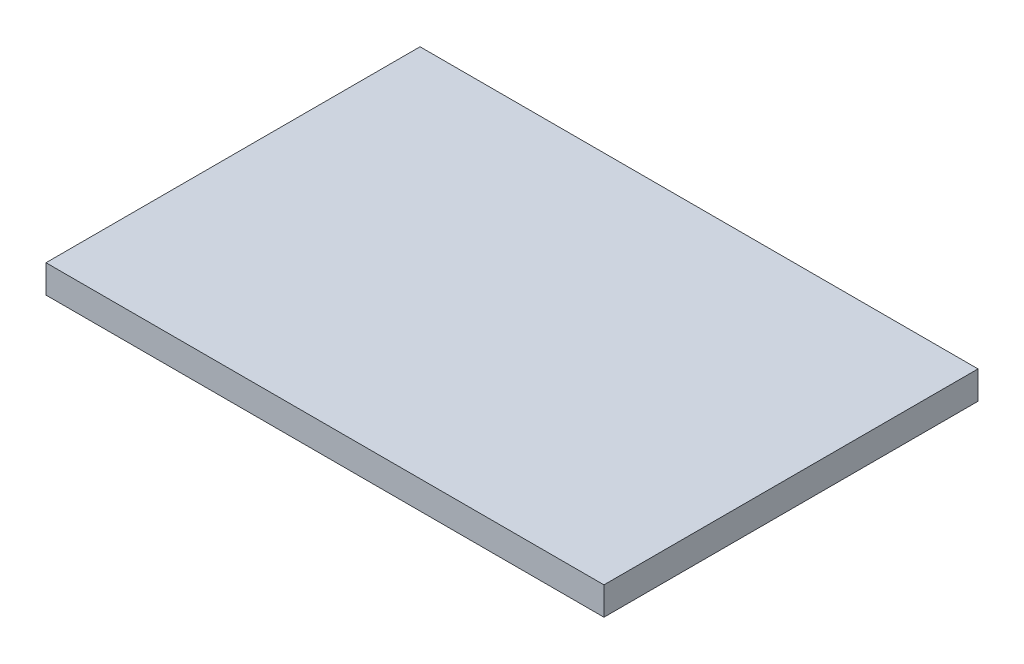
SolidWorks part; units mm, degrees
ref_plane "Alzado" through (0, 0, 0) normal (0, 0, 1) x (1, 0, 0)
ref_plane "Planta" through (0, 0, 0) normal (0, 1, 0) x (1, 0, 0)
ref_plane "Vista lateral" through (0, 0, 0) normal (1, 0, 0) x (0, 0, -1)
sketch "Croquis1" plane through (0, 0, 0) normal (0, 1, 0) x (1, 0, 0)
  line L1 (-179, 120) -> (179, 120)
  line L2 (-179, 120) -> (-179, -120)
  line L3 (-179, -120) -> (179, -120)
  line L4 (179, 120) -> (179, -120)
  line L5 (-179, 120) -> (179, -120) construction
  line L6 (-179, -120) -> (179, 120) construction
  point P0 (0, 0)
  dimension "D1" = 358
  dimension "D2" = 240
extrude "Saliente-Extruir1" add sketch "Croquis1" along normal blind 18
